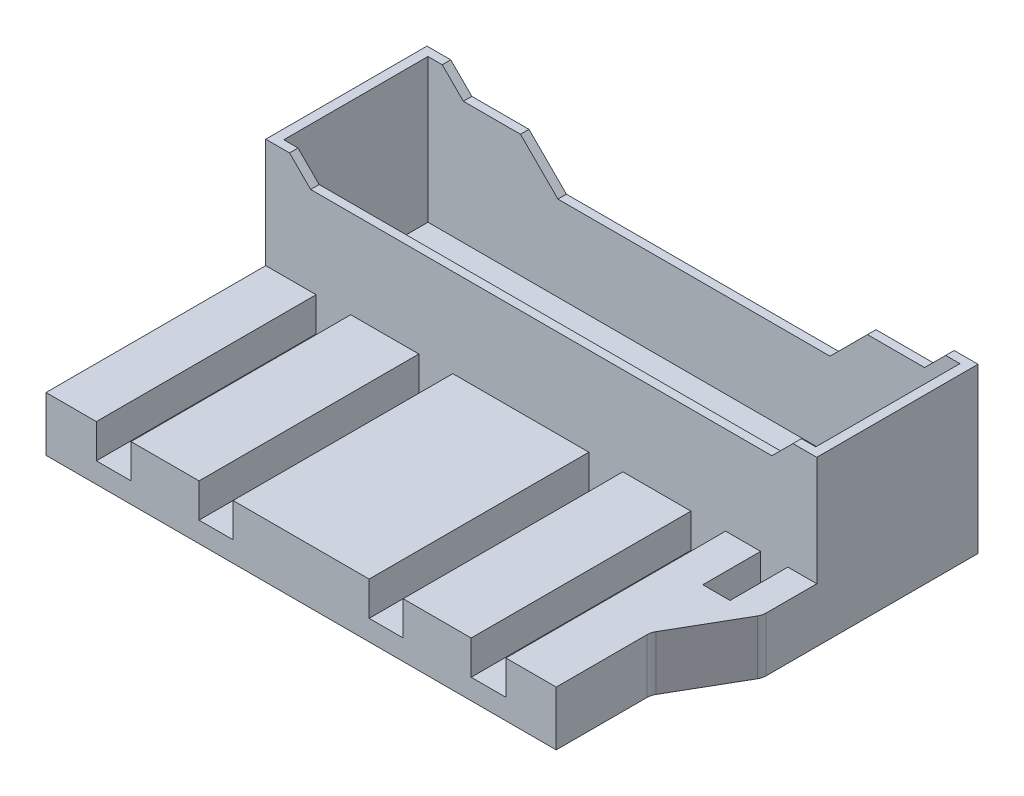
SolidWorks part; units mm, degrees
ref_plane "Front" through (0, 0, 0) normal (0, 0, 1) x (1, 0, 0)
ref_plane "Top" through (0, 0, 0) normal (0, 1, 0) x (1, 0, 0)
ref_plane "Right" through (0, 0, 0) normal (1, 0, 0) x (0, 0, -1)
sketch "Sketch1" plane through (0, 0, 0) normal (0, 1, 0) x (1, 0, 0)
  line L1 (-40.5, -11.85) -> (40.5, -11.85) construction
  line L2 (-40.5, -11.85) -> (-40.5, 11.85)
  line L3 (-40.5, 11.85) -> (0, 11.85)
  line L4 (40.5, -11.85) -> (40.5, 11.85)
  line L5 (-40.5, -11.85) -> (40.5, 11.85) construction
  line L6 (-40.5, 11.85) -> (40.5, -11.85) construction
  line L13 (0, 11.85) -> (40.5, 11.85)
  line L14 (-40.5, -11.85) -> (-40.5, -44.15)
  line L15 (-40.5, -44.15) -> (40.5, -44.15) construction
  line L16 (40.5, -44.15) -> (40.5, -11.85) construction
  line L17 (34.5, -44.15) -> (34.5, -30.2423)
  line L18 (34.5, -30.2423) -> (40.5, -19.85)
  line L19 (34.5, -44.15) -> (-40.5, -44.15)
  line L20 (40.5, -19.85) -> (40.5, -11.85)
  point P0 (0, 0)
  dimension "D1" = 81
  dimension "D2" = 32.3
  dimension "D3" = 30
  dimension "D4" = 23.7
  dimension "D5" = 6
  dimension "D6" = 8
extrude "Boss-Extrude1" add sketch "Sketch1" along normal blind 3
sketch "Sketch7" plane through (0, 3, 0) normal (0, 1, 0) x (1, 0, 0)
  line L0 (40.5, 11.85) -> (-40.5, 11.85) construction
  line L1 (-40.5, -11.85) -> (40.5, -11.85)
  line L2 (-40.5, -11.85) -> (-40.5, 11.85)
  line L3 (-40.5, 11.85) -> (40.5, 11.85)
  line L4 (40.5, -11.85) -> (40.5, 11.85)
  line L5 (-40.5, -11.85) -> (40.5, 11.85) construction
  line L6 (-40.5, 11.85) -> (40.5, -11.85) construction
  line L7 (-40.5, 11.85) -> (-40.5, -44.15) construction
  line L8 (40.5, -19.85) -> (40.5, 11.85) construction
  line L9 (39.1, 10.6) -> (-39.1, 10.6)
  line L10 (39.1, 10.6) -> (39.1, -10.6)
  line L11 (39.1, -10.6) -> (-39.1, -10.6)
  line L12 (-39.1, 10.6) -> (-39.1, -10.6)
  line L13 (39.1, 10.6) -> (-39.1, -10.6) construction
  line L14 (39.1, -10.6) -> (-39.1, 10.6) construction
  point P0 (0, 0)
  point P10 (0, 0)
  dimension "D1" = 1.4
  dimension "D2" = 1.25
  dimension "D3" = 1.25
  dimension "D4" = 1.4
  dimension "D5" = 23.7
extrude "Boss-Extrude4" add sketch "Sketch7" along normal blind 23.5
sketch "Sketch8" plane through (0, 3, 0) normal (0, 1, 0) x (1, 0, 0)
  line L5 (-39.1, -10.6) -> (39.1, 10.6) construction
  line L6 (-39.1, 10.6) -> (39.1, -10.6) construction
  line L11 (37.5, 2) -> (-37.5, -2) construction
  line L12 (37.5, -2) -> (-37.5, 2) construction
  line L15 (0, -11.85) -> (0, 11.85) construction
  line L16 (-40.5, -11.85) -> (40.5, -11.85) construction
  line L17 (40.5, 11.85) -> (-40.5, 11.85) construction
  line L18 (33.5, -2) -> (37.5, -2)
  line L19 (33.5, -10.6) -> (37.5, -10.6)
  line L33 (37.5, -2) -> (37.5, -10.6) construction
  line L34 (-39.1, -10.6) -> (33.5, -10.6)
  line L35 (-39.1, -10.6) -> (-39.1, 10.6)
  line L36 (-39.1, 10.6) -> (39.1, 10.6)
  line L37 (39.1, -10.6) -> (39.1, 10.6)
  line L38 (37.5, 2) -> (-37.5, 2)
  line L39 (37.5, 2) -> (37.5, -2)
  line L40 (33.5, -2) -> (-37.5, -2)
  line L41 (-37.5, 2) -> (-37.5, -2)
  line L42 (33.5, -2) -> (33.5, -10.6) construction
  line L43 (37.5, -10.6) -> (39.1, -10.6)
  point P0 (0, 0)
  point P10 (0, 0)
sketch "Sketch16" plane through (0, 0, -11.85) normal (0, 0, -1) x (-1, 0, 0)
  line L0 (-40.5, 26.5) -> (40.5, 26.5)
  line L2 (-40.5, 26.5) -> (40.5, 26.5) construction
  line L3 (40.5, 26.5) -> (40.5, 24.1)
  line L4 (40.5, 26.5) -> (40.5, 0) construction
  line L5 (40.5, 24.1) -> (37, 24.1)
  line L6 (37, 24.1) -> (33.9, 21)
  line L7 (33.9, 21) -> (25.5, 21)
  line L8 (25.5, 21) -> (20, 15.5)
  line L9 (20, 15.5) -> (-20, 15.5)
  line L10 (-20, 15.5) -> (-25.5, 21)
  line L11 (-25.5, 21) -> (-33.9, 21)
  line L12 (-33.9, 21) -> (-37, 24.1)
  line L13 (-37, 24.1) -> (-40.5, 24.1)
  line L14 (-40.5, 24.1) -> (-40.5, 26.5)
  line L15 (-40.5, 0) -> (40.5, 0) construction
  point P2 (0, 26.5)
  point P6 (0, 0)
  point P19 (0, 0)
  dimension "D1" = 45
  dimension "D2" = 3.5
  dimension "D3" = 2.4
  dimension "D4" = 5.5
  dimension "D5" = 15
  dimension "D6" = 11
  dimension "D7" = 26.5
extrude "Cut-Extrude7" cut sketch "Sketch16" against normal up to vertex
extrude "Cut-Extrude8" cut sketch "Sketch8" against normal blind 4 contours L40 L41 L38 L39 L18
sketch "Sketch14" plane through (0, 3, 0) normal (0, 1, 0) x (1, 0, 0)
  line L1 (40.5, -19.85) -> (40.5, 11.85) construction
  line L8 (-40.5, -11.85) -> (40.5, -11.85) construction
  line L9 (36.25, -11.85) -> (36.25, -20.35)
  line L10 (36.25, -20.35) -> (32.25, -20.35)
  line L11 (32.25, -20.35) -> (32.25, -11.85)
  line L13 (-40.5, -11.85) -> (40.5, -11.85) construction
  line L15 (0, 0) -> (0, -44.15) construction
  line L17 (36.25, -11.85) -> (36.25, 0.15)
  line L18 (36.25, 0.15) -> (32.25, 0.15)
  line L19 (32.25, 0.15) -> (32.25, -11.85)
  point P2 (0, 0)
  dimension "D1" = 4.25
  dimension "D2" = 8.5
  dimension "D3" = 4
  dimension "D4" = 12
extrude "Cut-Extrude9" cut sketch "Sketch14" against normal blind 4 contours L9 L10 L11 L19 L18 L17
sketch "Sketch17" plane through (0, 3, 0) normal (0, 1, 0) x (1, 0, 0)
  line L0 (32.25, -20.35) -> (36.25, -20.35)
  line L1 (-40.5, -44.15) -> (-33.1, -44.15)
  line L2 (-40.5, -44.15) -> (-40.5, -11.85)
  line L3 (-40.5, -11.85) -> (-33.1, -11.85)
  line L4 (34.5, -44.15) -> (34.5, -11.85) construction
  line L5 (-40.5, -44.15) -> (34.5, -11.85) construction
  line L6 (-40.5, -11.85) -> (34.5, -44.15) construction
  line L7 (36.25, -20.35) -> (32.25, -20.35) construction
  line L9 (36.25, -20.35) -> (36.25, -11.85)
  line L10 (32.25, -20.35) -> (32.25, -11.85)
  line L11 (32.25, -20.35) -> (32.25, -11.85) construction
  line L12 (36.25, -11.85) -> (34.5, -11.85) construction
  line L13 (-3, -44.15) -> (-3, -11.85) construction
  line L15 (-33.1, -44.15) -> (-33.1, -11.85)
  line L17 (-28, -44.15) -> (-28, -11.85)
  line L18 (-33.1, -44.15) -> (-28, -11.85) construction
  line L19 (-33.1, -11.85) -> (-28, -44.15) construction
  line L21 (-18, -44.15) -> (-18, -11.85)
  line L23 (-13, -44.15) -> (-13, -11.85)
  line L24 (-18, -44.15) -> (-13, -11.85) construction
  line L25 (-18, -11.85) -> (-13, -44.15) construction
  line L27 (22, -44.15) -> (22, -11.85)
  line L29 (27.1, -44.15) -> (27.1, -11.85)
  line L31 (7, -44.15) -> (7, -11.85)
  line L33 (12, -44.15) -> (12, -11.85)
  line L34 (-28, -11.85) -> (-18, -11.85)
  line L35 (-28, -44.15) -> (-18, -44.15)
  line L36 (-13, -11.85) -> (7, -11.85)
  line L37 (-13, -44.15) -> (7, -44.15)
  line L38 (12, -44.15) -> (22, -44.15)
  line L39 (27.1, -44.15) -> (34.5, -44.15)
  line L40 (27.1, -11.85) -> (32.25, -11.85)
  line L41 (12, -11.85) -> (22, -11.85)
  line L42 (36.25, -2) -> (36.25, -20.35) construction
  line L43 (34.5, -44.15) -> (34.5, -30.2423)
  line L44 (34.5, -30.2423) -> (40.5, -19.85)
  line L45 (40.5, -19.85) -> (40.5, -11.85) construction
  line L46 (34.5, -30.2423) -> (40.5, -19.85) construction
  line L47 (40.5, -19.85) -> (40.5, -11.85)
  line L48 (36.25, -11.85) -> (40.5, -11.85) construction
  line L49 (40.5, -11.85) -> (36.25, -11.85)
  point P0 (-3, -28)
  point P5 (-30.55, -28)
  point P15 (34.5, -32.1745)
  point P23 (-15.5, -28)
  point P39 (-3, -44.15)
  dimension "D1" = 10
  dimension "D2" = 25
  dimension "D3" = 5
  dimension "D4" = 5.1
extrude "Boss-Extrude5" add sketch "Sketch17" along normal blind 5
sketch "Sketch18" plane through (0, 0, 10.6) normal (0, 0, -1) x (-1, 0, 0)
  line L0 (40.5, 26.5) -> (40.5, 24.1)
  line L1 (39.1, 24.1) -> (40.5, 24.1) construction
  line L2 (40.5, 24.1) -> (40.5, 26.5) construction
  line L3 (40.5, 24.1) -> (37, 24.1)
  line L4 (37, 24.1) -> (33.9, 21)
  line L5 (33.9, 21) -> (-33.9, 21)
  line L6 (-33.9, 21) -> (-37, 24.1)
  line L7 (-37, 24.1) -> (-40.5, 24.1)
  line L9 (-40.5, 26.5) -> (-40.5, 24.1) construction
  line L10 (-40.5, 24.1) -> (-40.5, 26.5)
  line L11 (-40.5, 26.5) -> (40.5, 26.5)
  line L12 (-40.5, 24.1) -> (-37, 24.1) construction
  line L13 (40.5, 26.5) -> (-40.5, 26.5) construction
  point P23 (0, 0)
extrude "Cut-Extrude10" cut sketch "Sketch18" against normal up to vertex (1.25 mm away) up to point (-40.5, 26.5, 11.85)
fillet "Fillet1" radius 2 2 edges at (34.5, 4, 30.2423) (40.5, 4, 19.85)
